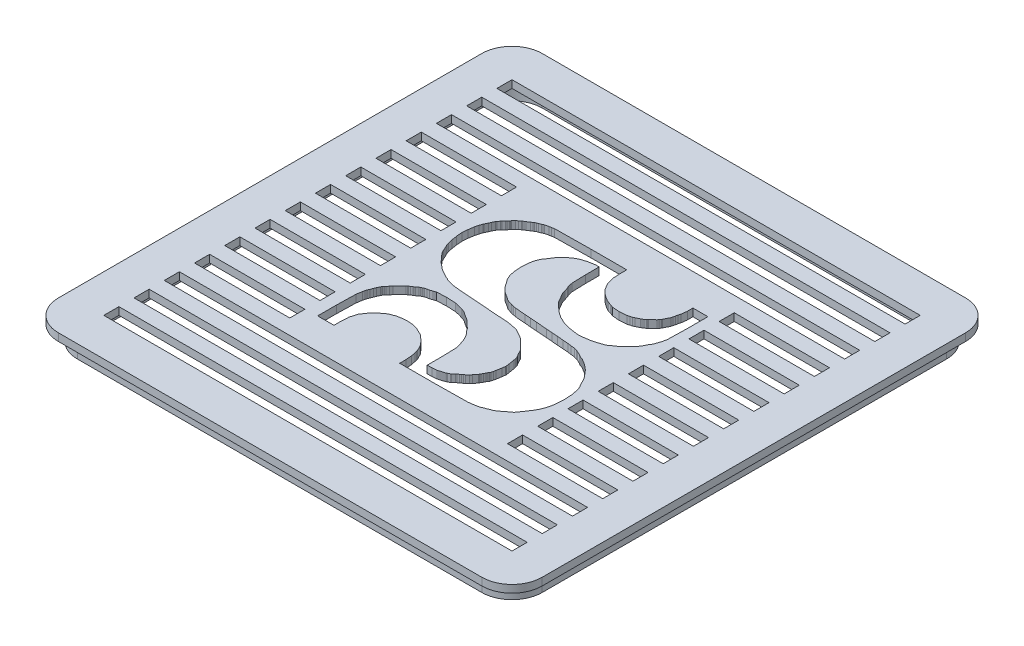
SolidWorks part; units mm, degrees
ref_plane "Front" through (0, 0, 0) normal (0, 0, 1) x (1, 0, 0)
ref_plane "Top" through (0, 0, 0) normal (0, 1, 0) x (1, 0, 0)
ref_plane "Right" through (0, 0, 0) normal (1, 0, 0) x (0, 0, -1)
sketch "Esquisse1" plane through (0, 0, 0) normal (0, 1, 0) x (1, 0, 0)
  line L1 (-50.8, 50.8) -> (50.8, 50.8)
  line L2 (-50.8, 50.8) -> (-50.8, -50.8)
  line L3 (-50.8, -50.8) -> (50.8, -50.8)
  line L4 (50.8, 50.8) -> (50.8, -50.8)
  line L5 (-50.8, 50.8) -> (50.8, -50.8) construction
  line L6 (-50.8, -50.8) -> (50.8, 50.8) construction
  point P0 (0, 0)
  dimension "D1" = 101.6
extrude "Boss.-Extru.1" add sketch "Esquisse1" along normal blind 1.5875
fillet "Congé1" radius 6.35 4 edges at (-50.8, 0.7937, -50.8) (50.8, 0.7937, -50.8) (-50.8, 0.7937, 50.8) (50.8, 0.7937, 50.8)
sketch "Esquisse2" plane through (0, 0, 0) normal (0, -1, 0) x (1, 0, 0)
  line L0 (-50.8, -44.45) -> (-50.8, 44.45) construction
  line L1 (-39.2906, 45.6406) -> (39.2906, 45.6406)
  line L2 (-45.6406, 39.2906) -> (-45.6406, -39.2906)
  line L3 (-39.2906, -45.6406) -> (39.2906, -45.6406)
  line L4 (45.6406, 39.2906) -> (45.6406, -39.2906)
  line L5 (-45.6406, 45.6406) -> (45.6406, -45.6406) construction
  line L6 (-45.6406, -45.6406) -> (45.6406, 45.6406) construction
  line L7 (-42.4656, 48.8156) -> (42.4656, 48.8156)
  line L8 (-48.8156, 42.4656) -> (-48.8156, -42.4656)
  line L9 (-42.4656, -48.8156) -> (42.4656, -48.8156)
  line L10 (48.8156, 42.4656) -> (48.8156, -42.4656)
  line L11 (-48.8156, 48.8156) -> (48.8156, -48.8156) construction
  line L12 (-48.8156, -48.8156) -> (48.8156, 48.8156) construction
  line L13 (44.45, -50.8) -> (-44.45, -50.8) construction
  arc A0 (-45.6406, -39.2906) -> (-39.2906, -45.6406) centre (-39.2906, -39.2906) ccw
  arc A1 (39.2906, -45.6406) -> (45.6406, -39.2906) centre (39.2906, -39.2906) ccw
  arc A2 (39.2906, 45.6406) -> (45.6406, 39.2906) centre (39.2906, 39.2906) cw
  arc A3 (-39.2906, 45.6406) -> (-45.6406, 39.2906) centre (-39.2906, 39.2906) ccw
  arc A4 (-48.8156, -42.4656) -> (-42.4656, -48.8156) centre (-42.4656, -42.4656) ccw
  arc A5 (42.4656, -48.8156) -> (48.8156, -42.4656) centre (42.4656, -42.4656) ccw
  arc A6 (42.4656, 48.8156) -> (48.8156, 42.4656) centre (42.4656, 42.4656) cw
  arc A7 (-42.4656, 48.8156) -> (-48.8156, 42.4656) centre (-42.4656, 42.4656) ccw
  point P0 (0, 0)
  point P6 (0, 0)
  dimension "D5" = 6.35
  dimension "D1" = 1.9844
  dimension "D2" = 1.9844
  dimension "D3" = 3.175
  dimension "D4" = 3.175
extrude "Boss.-Extru.2" add sketch "Esquisse2" along normal blind 3.175
sketch "Esquisse12" plane through (0, 1.5875, 0) normal (0, 1, 0) x (1, 0, 0)
  line L0 (-20.3148, -16.5337) -> (-20.2196, -12.5637)
  line L1 (-20.2196, -12.5637) -> (-20.1244, -11.9493)
  line L2 (-20.1244, -11.9493) -> (-20.0292, -11.3349)
  line L3 (-20.0292, -11.3349) -> (-19.934, -10.9568)
  line L4 (-19.934, -10.9568) -> (-19.8389, -10.5787)
  line L5 (-19.8389, -10.5787) -> (-19.7437, -10.3897)
  line L6 (-19.7437, -10.3897) -> (-19.6485, -10.2006)
  line L7 (-19.6485, -10.2006) -> (-19.5533, -9.917)
  line L8 (-19.5533, -9.917) -> (-19.4581, -9.6335)
  line L9 (-19.4581, -9.6335) -> (-19.3629, -9.3972)
  line L10 (-19.3629, -9.3972) -> (-19.2678, -9.1609)
  line L11 (-19.2678, -9.1609) -> (-19.1726, -8.9718)
  line L12 (-19.1726, -8.9718) -> (-19.0774, -8.7827)
  line L13 (-19.0774, -8.7827) -> (-18.9822, -8.5937)
  line L14 (-18.9822, -8.5937) -> (-18.887, -8.4046)
  line L15 (-18.887, -8.4046) -> (-18.7918, -8.2629)
  line L16 (-18.7918, -8.2629) -> (-18.6491, -8.1211)
  line L17 (-18.6491, -8.1211) -> (-18.5063, -7.9725)
  line L18 (-18.5063, -7.9725) -> (-18.1731, -7.5539)
  line L19 (-18.1731, -7.5539) -> (-17.84, -7.1336)
  line L20 (-17.84, -7.1336) -> (-16.4616, -5.758)
  line L21 (-16.4616, -5.758) -> (-16.317, -5.6635)
  line L22 (-16.317, -5.6635) -> (-16.1953, -5.5689)
  line L23 (-16.1953, -5.5689) -> (-15.9363, -5.3799)
  line L24 (-15.9363, -5.3799) -> (-15.6297, -5.1908)
  line L25 (-15.6297, -5.1908) -> (-15.4603, -5.0963)
  line L26 (-15.4603, -5.0963) -> (-15.3108, -5.0018)
  line L27 (-15.3108, -5.0018) -> (-14.8892, -4.6305)
  line L28 (-14.8892, -4.6305) -> (-14.6988, -4.5292)
  line L29 (-14.6988, -4.5292) -> (-14.5085, -4.4347)
  line L30 (-14.5085, -4.4347) -> (-14.3181, -4.3402)
  line L31 (-14.3181, -4.3402) -> (-14.1278, -4.2456)
  line L32 (-14.1278, -4.2456) -> (-13.6994, -4.1511)
  line L33 (-13.6994, -4.1511) -> (-13.2711, -4.0566)
  line L34 (-13.2711, -4.0566) -> (-12.9855, -3.9621)
  line L35 (-12.9855, -3.9621) -> (-12.7, -3.8676)
  line L36 (-12.7, -3.8676) -> (-12.4144, -3.773)
  line L37 (-12.4144, -3.773) -> (-12.1288, -3.6785)
  line L38 (-12.1288, -3.6785) -> (-10.1775, -3.584)
  line L39 (-10.1775, -3.584) -> (-8.2262, -3.6785)
  line L40 (-8.2262, -3.6785) -> (-7.7503, -3.773)
  line L41 (-7.7503, -3.773) -> (-7.2743, -3.8676)
  line L42 (-7.2743, -3.8676) -> (-6.9888, -3.9621)
  line L43 (-6.9888, -3.9621) -> (-6.7032, -4.0566)
  line L44 (-6.7032, -4.0566) -> (-6.3701, -4.1511)
  line L45 (-6.3701, -4.1511) -> (-6.0369, -4.2456)
  line L46 (-6.0369, -4.2456) -> (-5.8466, -4.3402)
  line L47 (-5.8466, -4.3402) -> (-5.6562, -4.4347)
  line L48 (-5.6562, -4.4347) -> (-5.4658, -4.5292)
  line L49 (-5.4658, -4.5292) -> (-5.2755, -4.671)
  line L50 (-5.2755, -4.671) -> (-5.1061, -4.8128)
  line L51 (-5.1061, -4.8128) -> (-4.7995, -5.0018)
  line L52 (-4.7995, -5.0018) -> (-4.4929, -5.1909)
  line L53 (-4.4929, -5.1909) -> (-4.3236, -5.2854)
  line L54 (-4.3236, -5.2854) -> (-4.1808, -5.3799)
  line L55 (-4.1808, -5.3799) -> (-4.038, -5.4744)
  line L56 (-4.038, -5.4744) -> (-3.8937, -5.569)
  line L57 (-3.8937, -5.569) -> (-2.3247, -7.0589)
  line L58 (-2.3247, -7.0589) -> (-2.1343, -7.2704)
  line L59 (-2.1343, -7.2704) -> (-1.944, -7.5748)
  line L60 (-1.944, -7.5748) -> (-1.7944, -7.743)
  line L61 (-1.7944, -7.743) -> (-1.3728, -8.188)
  line L62 (-1.3728, -8.188) -> (-1.1825, -8.4992)
  line L63 (-1.1825, -8.4992) -> (-0.9921, -8.8036)
  line L64 (-0.9921, -8.8036) -> (-0.8969, -8.9718)
  line L65 (-0.8969, -8.9718) -> (-0.8018, -9.1608)
  line L66 (-0.8018, -9.1608) -> (-0.7066, -9.3499)
  line L67 (-0.7066, -9.3499) -> (-0.6114, -9.5862)
  line L68 (-0.6114, -9.5862) -> (-0.5162, -9.8225)
  line L69 (-0.5162, -9.8225) -> (-0.421, -10.1061)
  line L70 (-0.421, -10.1061) -> (-0.3258, -10.3896)
  line L71 (-0.3258, -10.3896) -> (-0.2307, -10.6732)
  line L72 (-0.2307, -10.6732) -> (-0.1355, -10.9568)
  line L73 (-0.1355, -10.9568) -> (-0.0403, -11.3349)
  line L74 (-0.0403, -11.3349) -> (0.0549, -11.713)
  line L75 (0.0549, -11.713) -> (0.1501, -14.8322)
  line L76 (0.1501, -14.8322) -> (0.1501, -17.951)
  line L77 (0.1501, -17.951) -> (1.1496, -17.951)
  line L78 (1.1496, -17.951) -> (2.149, -17.8565)
  line L79 (2.149, -17.8565) -> (2.4346, -17.762)
  line L80 (2.4346, -17.762) -> (2.7201, -17.6674)
  line L81 (2.7201, -17.6674) -> (3.0533, -17.5729)
  line L82 (3.0533, -17.5729) -> (3.3864, -17.4784)
  line L83 (3.3864, -17.4784) -> (3.5768, -17.3839)
  line L84 (3.5768, -17.3839) -> (3.7672, -17.2893)
  line L85 (3.7672, -17.2893) -> (3.9575, -17.1948)
  line L86 (3.9575, -17.1948) -> (4.1479, -17.1003)
  line L87 (4.1479, -17.1003) -> (4.2975, -17.0058)
  line L88 (4.2975, -17.0058) -> (4.719, -16.5872)
  line L89 (4.719, -16.5872) -> (4.8884, -16.4386)
  line L90 (4.8884, -16.4386) -> (5.1949, -16.2496)
  line L91 (5.1949, -16.2496) -> (5.4329, -16.0606)
  line L92 (5.4329, -16.0606) -> (5.6709, -15.8715)
  line L93 (5.6709, -15.8715) -> (5.9366, -15.6825)
  line L94 (5.9366, -15.6825) -> (6.3372, -15.3044)
  line L95 (6.3372, -15.3044) -> (6.6678, -14.9263)
  line L96 (6.6678, -14.9263) -> (7.1938, -14.2689)
  line L97 (7.1938, -14.2689) -> (7.289, -14.0756)
  line L98 (7.289, -14.0756) -> (7.3842, -13.9074)
  line L99 (7.3842, -13.9074) -> (7.5746, -13.603)
  line L100 (7.5746, -13.603) -> (7.7649, -13.204)
  line L101 (7.7649, -13.204) -> (7.9077, -12.9413)
  line L102 (7.9077, -12.9413) -> (8.0505, -12.7522)
  line L103 (8.0505, -12.7522) -> (8.1457, -12.5632)
  line L104 (8.1457, -12.5632) -> (8.2408, -12.1378)
  line L105 (8.2408, -12.1378) -> (8.336, -11.7125)
  line L106 (8.336, -11.7125) -> (8.4312, -11.1453)
  line L107 (8.4312, -11.1453) -> (8.5264, -10.5782)
  line L108 (8.5264, -10.5782) -> (8.6216, -9.8693)
  line L109 (8.6216, -9.8693) -> (8.5264, -9.1604)
  line L110 (8.5264, -9.1604) -> (8.4312, -8.546)
  line L111 (8.4312, -8.546) -> (8.336, -7.9316)
  line L112 (8.336, -7.9316) -> (8.2408, -7.5535)
  line L113 (8.2408, -7.5535) -> (8.1457, -7.1754)
  line L114 (8.1457, -7.1754) -> (8.0505, -6.9391)
  line L115 (8.0505, -6.9391) -> (7.9077, -6.7028)
  line L116 (7.9077, -6.7028) -> (7.7649, -6.5137)
  line L117 (7.7649, -6.5137) -> (7.6698, -6.3246)
  line L118 (7.6698, -6.3246) -> (7.5746, -6.1356)
  line L119 (7.5746, -6.1356) -> (7.4794, -5.9465)
  line L120 (7.4794, -5.9465) -> (7.3842, -5.7575)
  line L121 (7.3842, -5.7575) -> (7.289, -5.5684)
  line L122 (7.289, -5.5684) -> (7.1938, -5.4223)
  line L123 (7.1938, -5.4223) -> (6.6271, -4.8122)
  line L124 (6.6271, -4.8122) -> (6.5275, -4.7157)
  line L125 (6.5275, -4.7157) -> (5.4084, -3.5834)
  line L126 (5.4084, -3.5834) -> (5.1949, -3.3944)
  line L127 (5.1949, -3.3944) -> (4.9094, -3.2053)
  line L128 (4.9094, -3.2053) -> (4.6238, -3.0163)
  line L129 (4.6238, -3.0163) -> (4.3172, -2.8272)
  line L130 (4.3172, -2.8272) -> (4.1479, -2.7327)
  line L131 (4.1479, -2.7327) -> (3.9575, -2.6382)
  line L132 (3.9575, -2.6382) -> (3.7671, -2.5437)
  line L133 (3.7671, -2.5437) -> (3.5768, -2.4491)
  line L134 (3.5768, -2.4491) -> (3.3864, -2.3074)
  line L135 (3.3864, -2.3074) -> (3.0533, -2.1656)
  line L136 (3.0533, -2.1656) -> (2.7201, -2.0711)
  line L137 (2.7201, -2.0711) -> (2.3394, -1.9765)
  line L138 (2.3394, -1.9765) -> (1.9586, -1.882)
  line L139 (1.9586, -1.882) -> (1.3875, -1.7875)
  line L140 (1.3875, -1.7875) -> (0.8164, -1.693)
  line L141 (0.8164, -1.693) -> (-0.5638, -1.5985)
  line L142 (-0.5638, -1.5985) -> (-1.944, -1.504)
  line L143 (-1.944, -1.504) -> (-3.2291, -1.4094)
  line L144 (-3.2291, -1.4094) -> (-4.5141, -1.3149)
  line L145 (-4.5141, -1.3149) -> (-5.7991, -1.2204)
  line L146 (-5.7991, -1.2204) -> (-7.0841, -1.1259)
  line L147 (-7.0841, -1.1259) -> (-8.3691, -1.0314)
  line L148 (-8.3691, -1.0314) -> (-9.6541, -0.9368)
  line L149 (-9.6541, -0.9368) -> (-10.606, -0.8423)
  line L150 (-10.606, -0.8423) -> (-11.5579, -0.7478)
  line L151 (-11.5579, -0.7478) -> (-11.9386, -0.6533)
  line L152 (-11.9386, -0.6533) -> (-12.3194, -0.5588)
  line L153 (-12.3194, -0.5588) -> (-12.7001, -0.4642)
  line L154 (-12.7001, -0.4642) -> (-13.0809, -0.3697)
  line L155 (-13.0809, -0.3697) -> (-13.2712, -0.2752)
  line L156 (-13.2712, -0.2752) -> (-13.4616, -0.1334)
  line L157 (-13.4616, -0.1334) -> (-13.7947, 0.0084)
  line L158 (-13.7947, 0.0084) -> (-14.1279, 0.1501)
  line L159 (-14.1279, 0.1501) -> (-14.3183, 0.2919)
  line L160 (-14.3183, 0.2919) -> (-14.5086, 0.3865)
  line L161 (-14.5086, 0.3865) -> (-14.699, 0.481)
  line L162 (-14.699, 0.481) -> (-14.8894, 0.5755)
  line L163 (-14.8894, 0.5755) -> (-15.0587, 0.67)
  line L164 (-15.0587, 0.67) -> (-15.3653, 0.8591)
  line L165 (-15.3653, 0.8591) -> (-15.6509, 1.0481)
  line L166 (-15.6509, 1.0481) -> (-15.9364, 1.2372)
  line L167 (-15.9364, 1.2372) -> (-16.1553, 1.4262)
  line L168 (-16.1553, 1.4262) -> (-16.6027, 1.8043)
  line L169 (-16.6027, 1.8043) -> (-17.078, 2.1824)
  line L170 (-17.078, 2.1824) -> (-17.4594, 2.6042)
  line L171 (-17.4594, 2.6042) -> (-18.2177, 3.4112)
  line L172 (-18.2177, 3.4112) -> (-18.3161, 3.5598)
  line L173 (-18.3161, 3.5598) -> (-18.69, 3.9784)
  line L174 (-18.69, 3.9784) -> (-18.792, 4.1674)
  line L175 (-18.792, 4.1674) -> (-18.8872, 4.3565)
  line L176 (-18.8872, 4.3565) -> (-18.9824, 4.5455)
  line L177 (-18.9824, 4.5455) -> (-19.0776, 4.7346)
  line L178 (-19.0776, 4.7346) -> (-19.1727, 4.9709)
  line L179 (-19.1727, 4.9709) -> (-19.2679, 5.2072)
  line L180 (-19.2679, 5.2072) -> (-19.3631, 5.3963)
  line L181 (-19.3631, 5.3963) -> (-19.4583, 5.5853)
  line L182 (-19.4583, 5.5853) -> (-19.5535, 5.7744)
  line L183 (-19.5535, 5.7744) -> (-19.6487, 5.9634)
  line L184 (-19.6487, 5.9634) -> (-19.7438, 6.247)
  line L185 (-19.7438, 6.247) -> (-19.839, 6.5306)
  line L186 (-19.839, 6.5306) -> (-19.9342, 6.9559)
  line L187 (-19.9342, 6.9559) -> (-20.0294, 7.3813)
  line L188 (-20.0294, 7.3813) -> (-20.1246, 7.9957)
  line L189 (-20.1246, 7.9957) -> (-20.2197, 8.6101)
  line L190 (-20.2197, 8.6101) -> (-20.3149, 9.7916)
  line L191 (-20.3149, 9.7916) -> (-20.2197, 10.9731)
  line L192 (-20.2197, 10.9731) -> (-20.1246, 11.5875)
  line L193 (-20.1246, 11.5875) -> (-20.0294, 12.2019)
  line L194 (-20.0294, 12.2019) -> (-19.9342, 12.58)
  line L195 (-19.9342, 12.58) -> (-19.839, 12.9581)
  line L196 (-19.839, 12.9581) -> (-19.7438, 13.2417)
  line L197 (-19.7438, 13.2417) -> (-19.6487, 13.5253)
  line L198 (-19.6487, 13.5253) -> (-19.5535, 13.7143)
  line L199 (-19.5535, 13.7143) -> (-19.4583, 13.9034)
  line L200 (-19.4583, 13.9034) -> (-19.3631, 14.0924)
  line L201 (-19.3631, 14.0924) -> (-19.2679, 14.2815)
  line L202 (-19.2679, 14.2815) -> (-19.1727, 14.5178)
  line L203 (-19.1727, 14.5178) -> (-19.0776, 14.7541)
  line L204 (-19.0776, 14.7541) -> (-18.9824, 14.9431)
  line L205 (-18.9824, 14.9431) -> (-18.8872, 15.1322)
  line L206 (-18.8872, 15.1322) -> (-18.792, 15.3212)
  line L207 (-18.792, 15.3212) -> (-18.69, 15.5103)
  line L208 (-18.69, 15.5103) -> (-18.3161, 15.9289)
  line L209 (-18.3161, 15.9289) -> (-18.2141, 16.0774)
  line L210 (-18.2141, 16.0774) -> (-17.8401, 16.4279)
  line L211 (-17.8401, 16.4279) -> (-17.6498, 16.6445)
  line L212 (-17.6498, 16.6445) -> (-17.4594, 16.9017)
  line L213 (-17.4594, 16.9017) -> (-17.3642, 17.0226)
  line L214 (-17.3642, 17.0226) -> (-17.269, 17.1712)
  line L215 (-17.269, 17.1712) -> (-16.8857, 17.5898)
  line L216 (-16.8857, 17.5898) -> (-16.5076, 17.8733)
  line L217 (-16.5076, 17.8733) -> (-16.1362, 18.1569)
  line L218 (-16.1362, 18.1569) -> (-16.0316, 18.2514)
  line L219 (-16.0316, 18.2514) -> (-15.8623, 18.3459)
  line L220 (-15.8623, 18.3459) -> (-15.5557, 18.535)
  line L221 (-15.5557, 18.535) -> (-15.2702, 18.724)
  line L222 (-15.2702, 18.724) -> (-14.9846, 18.9131)
  line L223 (-14.9846, 18.9131) -> (-14.678, 19.1021)
  line L224 (-14.678, 19.1021) -> (-14.5087, 19.2439)
  line L225 (-14.5087, 19.2439) -> (-14.2231, 19.3857)
  line L226 (-14.2231, 19.3857) -> (-13.9375, 19.4802)
  line L227 (-13.9375, 19.4802) -> (-13.6996, 19.5747)
  line L228 (-13.6996, 19.5747) -> (-13.4616, 19.6692)
  line L229 (-13.4616, 19.6692) -> (-13.2712, 19.7637)
  line L230 (-13.2712, 19.7637) -> (-13.0809, 19.8582)
  line L231 (-13.0809, 19.8582) -> (-12.7001, 19.9527)
  line L232 (-12.7001, 19.9527) -> (-12.3194, 20.0473)
  line L233 (-12.3194, 20.0473) -> (-11.7959, 20.1418)
  line L234 (-11.7959, 20.1418) -> (-11.2723, 20.2363)
  line L235 (-11.2723, 20.2363) -> (-3.7526, 20.3308)
  line L236 (-3.7526, 20.3308) -> (3.7672, 20.3304)
  line L237 (3.7672, 20.3304) -> (3.7672, 18.7706)
  line L238 (3.7672, 18.7706) -> (3.8624, 17.2109)
  line L239 (3.8624, 17.2109) -> (3.9575, 16.8801)
  line L240 (3.9575, 16.8801) -> (4.0527, 16.5493)
  line L241 (4.0527, 16.5493) -> (4.1479, 16.2184)
  line L242 (4.1479, 16.2184) -> (4.2431, 15.8876)
  line L243 (4.2431, 15.8876) -> (4.3383, 15.6986)
  line L244 (4.3383, 15.6986) -> (4.4335, 15.5095)
  line L245 (4.4335, 15.5095) -> (4.5286, 15.3413)
  line L246 (4.5286, 15.3413) -> (4.719, 15.0369)
  line L247 (4.719, 15.0369) -> (4.9094, 14.7325)
  line L248 (4.9094, 14.7325) -> (5.0045, 14.5643)
  line L249 (5.0045, 14.5643) -> (5.0997, 14.463)
  line L250 (5.0997, 14.463) -> (5.4323, 14.0917)
  line L251 (5.4323, 14.0917) -> (5.9564, 13.6191)
  line L252 (5.9564, 13.6191) -> (6.5955, 13.1464)
  line L253 (6.5955, 13.1464) -> (6.9083, 12.9574)
  line L254 (6.9083, 12.9574) -> (7.2148, 12.7683)
  line L255 (7.2148, 12.7683) -> (7.3842, 12.6738)
  line L256 (7.3842, 12.6738) -> (7.5746, 12.5793)
  line L257 (7.5746, 12.5793) -> (7.7649, 12.4848)
  line L258 (7.7649, 12.4848) -> (8.0981, 12.3903)
  line L259 (8.0981, 12.3903) -> (8.4312, 12.2958)
  line L260 (8.4312, 12.2958) -> (8.7168, 12.2013)
  line L261 (8.7168, 12.2013) -> (9.0023, 12.0595)
  line L262 (9.0023, 12.0595) -> (10.5729, 11.9177)
  line L263 (10.5729, 11.9177) -> (12.1435, 12.0595)
  line L264 (12.1435, 12.0595) -> (12.5718, 12.2013)
  line L265 (12.5718, 12.2013) -> (13.0002, 12.2958)
  line L266 (13.0002, 12.2958) -> (13.1905, 12.3903)
  line L267 (13.1905, 12.3903) -> (13.3809, 12.4848)
  line L268 (13.3809, 12.4848) -> (13.5713, 12.5793)
  line L269 (13.5713, 12.5793) -> (13.7616, 12.6738)
  line L270 (13.7616, 12.6738) -> (13.952, 12.7683)
  line L271 (13.952, 12.7683) -> (14.1424, 12.8629)
  line L272 (14.1424, 12.8629) -> (14.3117, 12.9574)
  line L273 (14.3117, 12.9574) -> (14.6183, 13.1464)
  line L274 (14.6183, 13.1464) -> (14.8773, 13.3355)
  line L275 (14.8773, 13.3355) -> (14.999, 13.43)
  line L276 (14.999, 13.43) -> (15.0967, 13.5245)
  line L277 (15.0967, 13.5245) -> (16.0461, 14.4464)
  line L278 (16.0461, 14.4464) -> (16.2365, 14.6588)
  line L279 (16.2365, 14.6588) -> (16.4268, 14.9632)
  line L280 (16.4268, 14.9632) -> (16.522, 15.1314)
  line L281 (16.522, 15.1314) -> (16.6172, 15.3204)
  line L282 (16.6172, 15.3204) -> (16.7124, 15.5095)
  line L283 (16.7124, 15.5095) -> (16.8076, 15.6985)
  line L284 (16.8076, 15.6985) -> (16.9027, 15.8876)
  line L285 (16.9027, 15.8876) -> (16.9979, 16.0766)
  line L286 (16.9979, 16.0766) -> (17.0931, 16.2657)
  line L287 (17.0931, 16.2657) -> (17.1883, 16.6438)
  line L288 (17.1883, 16.6438) -> (17.2835, 17.0219)
  line L289 (17.2835, 17.0219) -> (17.3787, 17.4945)
  line L290 (17.3787, 17.4945) -> (17.5214, 17.9671)
  line L291 (17.5214, 17.9671) -> (17.6642, 19.1486)
  line L292 (17.6642, 19.1486) -> (17.6642, 20.3304)
  line L293 (17.6642, 20.3304) -> (19.2348, 20.3304)
  line L294 (19.2348, 20.3304) -> (20.8053, 20.3304)
  line L295 (20.8053, 20.3304) -> (20.8053, 16.1241)
  line L296 (20.8053, 16.1241) -> (20.7102, 11.9179)
  line L297 (20.7102, 11.9179) -> (20.615, 11.4452)
  line L298 (20.615, 11.4452) -> (20.5198, 10.9726)
  line L299 (20.5198, 10.9726) -> (20.4246, 10.6891)
  line L300 (20.4246, 10.6891) -> (20.3294, 10.4055)
  line L301 (20.3294, 10.4055) -> (20.2342, 10.1219)
  line L302 (20.2342, 10.1219) -> (20.1391, 9.8383)
  line L303 (20.1391, 9.8383) -> (20.0439, 9.602)
  line L304 (20.0439, 9.602) -> (19.9011, 9.3657)
  line L305 (19.9011, 9.3657) -> (19.7583, 9.1767)
  line L306 (19.7583, 9.1767) -> (19.6632, 8.9876)
  line L307 (19.6632, 8.9876) -> (19.568, 8.7986)
  line L308 (19.568, 8.7986) -> (19.4728, 8.6095)
  line L309 (19.4728, 8.6095) -> (19.3776, 8.4205)
  line L310 (19.3776, 8.4205) -> (19.2824, 8.2314)
  line L311 (19.2824, 8.2314) -> (19.1872, 8.0896)
  line L312 (19.1872, 8.0896) -> (19.0921, 7.9478)
  line L313 (19.0921, 7.9478) -> (18.9969, 7.7797)
  line L314 (18.9969, 7.7797) -> (18.8065, 7.4752)
  line L315 (18.8065, 7.4752) -> (18.6161, 7.2633)
  line L316 (18.6161, 7.2633) -> (17.5174, 6.1519)
  line L317 (17.5174, 6.1519) -> (16.998, 5.6793)
  line L318 (16.998, 5.6793) -> (16.3854, 5.2067)
  line L319 (16.3854, 5.2067) -> (16.2365, 5.1122)
  line L320 (16.2365, 5.1122) -> (16.0461, 5.0176)
  line L321 (16.0461, 5.0176) -> (15.8557, 4.9164)
  line L322 (15.8557, 4.9164) -> (15.4342, 4.545)
  line L323 (15.4342, 4.545) -> (15.2846, 4.4505)
  line L324 (15.2846, 4.4505) -> (14.999, 4.356)
  line L325 (14.999, 4.356) -> (14.7135, 4.2614)
  line L326 (14.7135, 4.2614) -> (14.4279, 4.1669)
  line L327 (14.4279, 4.1669) -> (14.1424, 4.0724)
  line L328 (14.1424, 4.0724) -> (13.8568, 3.9779)
  line L329 (13.8568, 3.9779) -> (13.5713, 3.8834)
  line L330 (13.5713, 3.8834) -> (13.1905, 3.7888)
  line L331 (13.1905, 3.7888) -> (12.8098, 3.6943)
  line L332 (12.8098, 3.6943) -> (12.191, 3.5998)
  line L333 (12.191, 3.5998) -> (11.5723, 3.5053)
  line L334 (11.5723, 3.5053) -> (10.5729, 3.4107)
  line L335 (10.5729, 3.4107) -> (9.5734, 3.5053)
  line L336 (9.5734, 3.5053) -> (9.0023, 3.5998)
  line L337 (9.0023, 3.5998) -> (8.4312, 3.6943)
  line L338 (8.4312, 3.6943) -> (8.0029, 3.7888)
  line L339 (8.0029, 3.7888) -> (7.5745, 3.8834)
  line L340 (7.5745, 3.8834) -> (7.289, 3.9779)
  line L341 (7.289, 3.9779) -> (7.0034, 4.0724)
  line L342 (7.0034, 4.0724) -> (6.7654, 4.1669)
  line L343 (6.7654, 4.1669) -> (6.5275, 4.2614)
  line L344 (6.5275, 4.2614) -> (6.3371, 4.356)
  line L345 (6.3371, 4.356) -> (6.1467, 4.4505)
  line L346 (6.1467, 4.4505) -> (5.9564, 4.545)
  line L347 (5.9564, 4.545) -> (5.766, 4.6395)
  line L348 (5.766, 4.6395) -> (5.528, 4.7341)
  line L349 (5.528, 4.7341) -> (5.2901, 4.8758)
  line L350 (5.2901, 4.8758) -> (5.1207, 5.0176)
  line L351 (5.1207, 5.0176) -> (4.8141, 5.2067)
  line L352 (4.8141, 5.2067) -> (4.5506, 5.3957)
  line L353 (4.5506, 5.3957) -> (3.7671, 6.0574)
  line L354 (3.7671, 6.0574) -> (3.0535, 6.7191)
  line L355 (3.0535, 6.7191) -> (2.5297, 7.2819)
  line L356 (2.5297, 7.2819) -> (2.4345, 7.3807)
  line L357 (2.4345, 7.3807) -> (2.3393, 7.5489)
  line L358 (2.3393, 7.5489) -> (2.1489, 7.8533)
  line L359 (2.1489, 7.8533) -> (1.9586, 8.1842)
  line L360 (1.9586, 8.1842) -> (1.7682, 8.515)
  line L361 (1.7682, 8.515) -> (1.5778, 8.8194)
  line L362 (1.5778, 8.8194) -> (1.4827, 8.9876)
  line L363 (1.4827, 8.9876) -> (1.3875, 9.1766)
  line L364 (1.3875, 9.1766) -> (1.2923, 9.3657)
  line L365 (1.2923, 9.3657) -> (1.1971, 9.6965)
  line L366 (1.1971, 9.6965) -> (1.1019, 10.0274)
  line L367 (1.1019, 10.0274) -> (1.0067, 10.3109)
  line L368 (1.0067, 10.3109) -> (0.9116, 10.5945)
  line L369 (0.9116, 10.5945) -> (0.8164, 10.8781)
  line L370 (0.8164, 10.8781) -> (0.6736, 11.1616)
  line L371 (0.6736, 11.1616) -> (0.5308, 11.6815)
  line L372 (0.5308, 11.6815) -> (0.4357, 12.2014)
  line L373 (0.4357, 12.2014) -> (0.3405, 15.0844)
  line L374 (0.3405, 15.0844) -> (0.3405, 17.9674)
  line L375 (0.3405, 17.9674) -> (-0.3259, 17.9674)
  line L376 (-0.3259, 17.9674) -> (-0.9922, 17.8729)
  line L377 (-0.9922, 17.8729) -> (-1.4681, 17.7784)
  line L378 (-1.4681, 17.7784) -> (-1.9441, 17.6839)
  line L379 (-1.9441, 17.6839) -> (-2.2296, 17.5893)
  line L380 (-2.2296, 17.5893) -> (-2.5152, 17.4948)
  line L381 (-2.5152, 17.4948) -> (-2.8008, 17.4003)
  line L382 (-2.8008, 17.4003) -> (-3.0863, 17.3058)
  line L383 (-3.0863, 17.3058) -> (-3.2767, 17.2113)
  line L384 (-3.2767, 17.2113) -> (-3.467, 17.1168)
  line L385 (-3.467, 17.1168) -> (-3.6574, 17.0223)
  line L386 (-3.6574, 17.0223) -> (-3.8478, 16.921)
  line L387 (-3.8478, 16.921) -> (-4.3169, 16.5497)
  line L388 (-4.3169, 16.5497) -> (-4.5141, 16.4508)
  line L389 (-4.5141, 16.4508) -> (-5.0834, 15.888)
  line L390 (-5.0834, 15.888) -> (-6.0371, 14.9189)
  line L391 (-6.0371, 14.9189) -> (-6.2274, 14.6592)
  line L392 (-6.2274, 14.6592) -> (-6.4178, 14.3075)
  line L393 (-6.4178, 14.3075) -> (-6.5198, 14.0921)
  line L394 (-6.5198, 14.0921) -> (-6.8937, 13.6735)
  line L395 (-6.8937, 13.6735) -> (-6.9889, 13.5249)
  line L396 (-6.9889, 13.5249) -> (-7.0841, 13.3359)
  line L397 (-7.0841, 13.3359) -> (-7.1793, 13.1468)
  line L398 (-7.1793, 13.1468) -> (-7.2745, 12.9578)
  line L399 (-7.2745, 12.9578) -> (-7.3696, 12.7687)
  line L400 (-7.3696, 12.7687) -> (-7.4648, 12.4852)
  line L401 (-7.4648, 12.4852) -> (-7.56, 12.2016)
  line L402 (-7.56, 12.2016) -> (-7.6552, 11.7762)
  line L403 (-7.6552, 11.7762) -> (-7.7504, 11.3509)
  line L404 (-7.7504, 11.3509) -> (-7.8456, 9.7913)
  line L405 (-7.8456, 9.7913) -> (-7.7504, 8.2316)
  line L406 (-7.7504, 8.2316) -> (-7.6552, 7.8063)
  line L407 (-7.6552, 7.8063) -> (-7.56, 7.3809)
  line L408 (-7.56, 7.3809) -> (-7.4648, 7.0501)
  line L409 (-7.4648, 7.0501) -> (-7.3696, 6.7193)
  line L410 (-7.3696, 6.7193) -> (-7.2745, 6.5302)
  line L411 (-7.2745, 6.5302) -> (-7.1793, 6.3412)
  line L412 (-7.1793, 6.3412) -> (-7.0841, 6.1521)
  line L413 (-7.0841, 6.1521) -> (-6.9889, 5.9631)
  line L414 (-6.9889, 5.9631) -> (-6.8937, 5.8145)
  line L415 (-6.8937, 5.8145) -> (-6.5198, 5.3959)
  line L416 (-6.5198, 5.3959) -> (-6.4178, 5.2069)
  line L417 (-6.4178, 5.2069) -> (-6.3226, 5.0178)
  line L418 (-6.3226, 5.0178) -> (-6.2274, 4.8969)
  line L419 (-6.2274, 4.8969) -> (-6.0371, 4.6397)
  line L420 (-6.0371, 4.6397) -> (-5.8467, 4.3794)
  line L421 (-5.8467, 4.3794) -> (-5.079, 3.6)
  line L422 (-5.079, 3.6) -> (-4.7045, 3.3164)
  line L423 (-4.7045, 3.3164) -> (-4.259, 3.0328)
  line L424 (-4.259, 3.0328) -> (-3.943, 2.8438)
  line L425 (-3.943, 2.8438) -> (-3.6364, 2.6547)
  line L426 (-3.6364, 2.6547) -> (-3.4671, 2.513)
  line L427 (-3.4671, 2.513) -> (-3.2767, 2.3712)
  line L428 (-3.2767, 2.3712) -> (-3.0863, 2.2766)
  line L429 (-3.0863, 2.2766) -> (-2.8008, 2.1821)
  line L430 (-2.8008, 2.1821) -> (-2.5152, 2.0876)
  line L431 (-2.5152, 2.0876) -> (-2.2296, 1.9931)
  line L432 (-2.2296, 1.9931) -> (-1.9441, 1.8986)
  line L433 (-1.9441, 1.8986) -> (-1.4682, 1.804)
  line L434 (-1.4682, 1.804) -> (-0.9922, 1.7095)
  line L435 (-0.9922, 1.7095) -> (0.1024, 1.615)
  line L436 (0.1024, 1.615) -> (1.1971, 1.5205)
  line L437 (1.1971, 1.5205) -> (2.4821, 1.426)
  line L438 (2.4821, 1.426) -> (3.7671, 1.3314)
  line L439 (3.7671, 1.3314) -> (4.9569, 1.2369)
  line L440 (4.9569, 1.2369) -> (6.1468, 1.1424)
  line L441 (6.1468, 1.1424) -> (7.3842, 1.0479)
  line L442 (7.3842, 1.0479) -> (8.6216, 0.9534)
  line L443 (8.6216, 0.9534) -> (9.8114, 0.8588)
  line L444 (9.8114, 0.8588) -> (11.0013, 0.7643)
  line L445 (11.0013, 0.7643) -> (11.7628, 0.6698)
  line L446 (11.7628, 0.6698) -> (12.5243, 0.5753)
  line L447 (12.5243, 0.5753) -> (12.8574, 0.4808)
  line L448 (12.8574, 0.4808) -> (13.1906, 0.3862)
  line L449 (13.1906, 0.3862) -> (13.4761, 0.2917)
  line L450 (13.4761, 0.2917) -> (13.7617, 0.1499)
  line L451 (13.7617, 0.1499) -> (14.0472, 0.0082)
  line L452 (14.0472, 0.0082) -> (14.3328, -0.1336)
  line L453 (14.3328, -0.1336) -> (14.5232, -0.2754)
  line L454 (14.5232, -0.2754) -> (14.7135, -0.3699)
  line L455 (14.7135, -0.3699) -> (14.9991, -0.4644)
  line L456 (14.9991, -0.4644) -> (15.2847, -0.559)
  line L457 (15.2847, -0.559) -> (15.454, -0.6535)
  line L458 (15.454, -0.6535) -> (15.7606, -0.8426)
  line L459 (15.7606, -0.8426) -> (16.0672, -1.0316)
  line L460 (16.0672, -1.0316) -> (16.2365, -1.1261)
  line L461 (16.2365, -1.1261) -> (16.3855, -1.2206)
  line L462 (16.3855, -1.2206) -> (16.998, -1.6933)
  line L463 (16.998, -1.6933) -> (17.5629, -2.1659)
  line L464 (17.5629, -2.1659) -> (17.6643, -2.2656)
  line L465 (17.6643, -2.2656) -> (18.2354, -2.9221)
  line L466 (18.2354, -2.9221) -> (18.8065, -3.6049)
  line L467 (18.8065, -3.6049) -> (18.9969, -3.8673)
  line L468 (18.9969, -3.8673) -> (19.1873, -4.1717)
  line L469 (19.1873, -4.1717) -> (19.2824, -4.3399)
  line L470 (19.2824, -4.3399) -> (19.3776, -4.5553)
  line L471 (19.3776, -4.5553) -> (19.568, -4.907)
  line L472 (19.568, -4.907) -> (19.7584, -5.306)
  line L473 (19.7584, -5.306) -> (19.9011, -5.5687)
  line L474 (19.9011, -5.5687) -> (20.0439, -5.7578)
  line L475 (20.0439, -5.7578) -> (20.1391, -5.9468)
  line L476 (20.1391, -5.9468) -> (20.2343, -6.1359)
  line L477 (20.2343, -6.1359) -> (20.3295, -6.3249)
  line L478 (20.3295, -6.3249) -> (20.4246, -6.7503)
  line L479 (20.4246, -6.7503) -> (20.5198, -7.1756)
  line L480 (20.5198, -7.1756) -> (20.615, -7.6482)
  line L481 (20.615, -7.6482) -> (20.7102, -8.1209)
  line L482 (20.7102, -8.1209) -> (20.8054, -9.8223)
  line L483 (20.8054, -9.8223) -> (20.7102, -11.5237)
  line L484 (20.7102, -11.5237) -> (20.615, -12.0436)
  line L485 (20.615, -12.0436) -> (20.5198, -12.5634)
  line L486 (20.5198, -12.5634) -> (20.4246, -12.9415)
  line L487 (20.4246, -12.9415) -> (20.3295, -13.3196)
  line L488 (20.3295, -13.3196) -> (20.2343, -13.5087)
  line L489 (20.2343, -13.5087) -> (20.1391, -13.6977)
  line L490 (20.1391, -13.6977) -> (20.0439, -14.0286)
  line L491 (20.0439, -14.0286) -> (19.9011, -14.3594)
  line L492 (19.9011, -14.3594) -> (19.7584, -14.5484)
  line L493 (19.7584, -14.5484) -> (19.6632, -14.7375)
  line L494 (19.6632, -14.7375) -> (19.568, -14.9057)
  line L495 (19.568, -14.9057) -> (19.3776, -15.2101)
  line L496 (19.3776, -15.2101) -> (19.1873, -15.4937)
  line L497 (19.1873, -15.4937) -> (18.9969, -15.7772)
  line L498 (18.9969, -15.7772) -> (18.8065, -16.0608)
  line L499 (18.8065, -16.0608) -> (18.6162, -16.3444)
  line L500 (18.6162, -16.3444) -> (18.4258, -16.6109)
  line L501 (18.4258, -16.6109) -> (18.1402, -17.006)
  line L502 (18.1402, -17.006) -> (17.8547, -17.4221)
  line L503 (17.8547, -17.4221) -> (17.6581, -17.5732)
  line L504 (17.6581, -17.5732) -> (16.998, -18.0458)
  line L505 (16.998, -18.0458) -> (16.4065, -18.5184)
  line L506 (16.4065, -18.5184) -> (16.1413, -18.7075)
  line L507 (16.1413, -18.7075) -> (15.8347, -18.8965)
  line L508 (15.8347, -18.8965) -> (15.6654, -19.0383)
  line L509 (15.6654, -19.0383) -> (15.475, -19.1801)
  line L510 (15.475, -19.1801) -> (15.2847, -19.2746)
  line L511 (15.2847, -19.2746) -> (14.9991, -19.3691)
  line L512 (14.9991, -19.3691) -> (14.7135, -19.4637)
  line L513 (14.7135, -19.4637) -> (14.5232, -19.5582)
  line L514 (14.5232, -19.5582) -> (14.3328, -19.6527)
  line L515 (14.3328, -19.6527) -> (14.0473, -19.7472)
  line L516 (14.0473, -19.7472) -> (13.7617, -19.8417)
  line L517 (13.7617, -19.8417) -> (13.5713, -19.9363)
  line L518 (13.5713, -19.9363) -> (13.3809, -20.0308)
  line L519 (13.3809, -20.0308) -> (12.9526, -20.1253)
  line L520 (12.9526, -20.1253) -> (12.5243, -20.2198)
  line L521 (12.5243, -20.2198) -> (11.858, -20.3143)
  line L522 (11.858, -20.3143) -> (11.1917, -20.4089)
  line L523 (11.1917, -20.4089) -> (4.0527, -20.5034)
  line L524 (4.0527, -20.5034) -> (-3.0859, -20.5029)
  line L525 (-3.0859, -20.5029) -> (-3.0859, -19.2273)
  line L526 (-3.0859, -19.2273) -> (-3.1811, -17.9513)
  line L527 (-3.1811, -17.9513) -> (-3.2763, -17.4787)
  line L528 (-3.2763, -17.4787) -> (-3.3715, -17.006)
  line L529 (-3.3715, -17.006) -> (-3.4667, -16.6279)
  line L530 (-3.4667, -16.6279) -> (-3.5619, -16.2499)
  line L531 (-3.5619, -16.2499) -> (-3.657, -16.0608)
  line L532 (-3.657, -16.0608) -> (-3.7522, -15.8718)
  line L533 (-3.7522, -15.8718) -> (-3.8474, -15.6827)
  line L534 (-3.8474, -15.6827) -> (-3.9426, -15.4936)
  line L535 (-3.9426, -15.4936) -> (-4.0378, -15.3046)
  line L536 (-4.0378, -15.3046) -> (-4.1397, -15.1155)
  line L537 (-4.1397, -15.1155) -> (-4.5137, -14.7178)
  line L538 (-4.5137, -14.7178) -> (-4.7041, -14.4539)
  line L539 (-4.7041, -14.4539) -> (-4.8944, -14.2415)
  line L540 (-4.8944, -14.2415) -> (-5.8704, -13.3196)
  line L541 (-5.8704, -13.3196) -> (-6.1319, -13.1305)
  line L542 (-6.1319, -13.1305) -> (-6.486, -12.9415)
  line L543 (-6.486, -12.9415) -> (-6.703, -12.847)
  line L544 (-6.703, -12.847) -> (-6.8933, -12.7525)
  line L545 (-6.8933, -12.7525) -> (-7.0837, -12.6579)
  line L546 (-7.0837, -12.6579) -> (-7.2741, -12.5634)
  line L547 (-7.2741, -12.5634) -> (-7.4645, -12.4689)
  line L548 (-7.4645, -12.4689) -> (-7.75, -12.3744)
  line L549 (-7.75, -12.3744) -> (-8.0356, -12.2799)
  line L550 (-8.0356, -12.2799) -> (-8.4163, -12.1853)
  line L551 (-8.4163, -12.1853) -> (-8.7971, -12.0908)
  line L552 (-8.7971, -12.0908) -> (-9.9393, -11.9963)
  line L553 (-9.9393, -11.9963) -> (-11.0815, -12.0908)
  line L554 (-11.0815, -12.0908) -> (-11.6051, -12.1853)
  line L555 (-11.6051, -12.1853) -> (-12.1286, -12.2799)
  line L556 (-12.1286, -12.2799) -> (-12.3189, -12.3744)
  line L557 (-12.3189, -12.3744) -> (-12.5093, -12.4689)
  line L558 (-12.5093, -12.4689) -> (-12.7949, -12.5634)
  line L559 (-12.7949, -12.5634) -> (-13.0804, -12.6579)
  line L560 (-13.0804, -12.6579) -> (-13.2498, -12.7525)
  line L561 (-13.2498, -12.7525) -> (-13.5564, -12.9415)
  line L562 (-13.5564, -12.9415) -> (-13.865, -13.1306)
  line L563 (-13.865, -13.1306) -> (-15.0793, -14.2229)
  line L564 (-15.0793, -14.2229) -> (-15.4601, -14.6429)
  line L565 (-15.4601, -14.6429) -> (-15.8408, -15.1554)
  line L566 (-15.8408, -15.1554) -> (-15.936, -15.3046)
  line L567 (-15.936, -15.3046) -> (-16.0312, -15.4937)
  line L568 (-16.0312, -15.4937) -> (-16.174, -15.6827)
  line L569 (-16.174, -15.6827) -> (-16.3167, -15.8718)
  line L570 (-16.3167, -15.8718) -> (-16.4119, -16.0608)
  line L571 (-16.4119, -16.0608) -> (-16.5071, -16.4389)
  line L572 (-16.5071, -16.4389) -> (-16.6023, -16.817)
  line L573 (-16.6023, -16.817) -> (-16.6975, -17.1006)
  line L574 (-16.6975, -17.1006) -> (-16.7927, -17.3841)
  line L575 (-16.7927, -17.3841) -> (-16.8878, -18.9438)
  line L576 (-16.8878, -18.9438) -> (-16.8878, -20.5029)
  line L577 (-16.8878, -20.5029) -> (-18.6012, -20.5029)
  line L578 (-18.6012, -20.5029) -> (-20.3145, -20.5029)
  line L579 (-20.3145, -20.5029) -> (-20.3148, -16.5337)
extrude "Enlèv. mat.-Extru.3" cut sketch "Esquisse12" against normal blind 3.175
sketch "Esquisse14" plane through (0, 0, 0) normal (0, -1, 0) x (1, 0, 0)
  line L0 (-42.8625, 36.5125) -> (42.8625, 36.5125)
  line L1 (-22.86, 22.86) -> (22.86, 22.86) construction
  line L2 (-22.86, 22.86) -> (-22.86, -22.86) construction
  line L3 (-22.86, -22.86) -> (22.86, -22.86) construction
  line L4 (22.86, 22.86) -> (22.86, -22.86) construction
  line L5 (-22.86, 22.86) -> (22.86, -22.86) construction
  line L6 (-22.86, -22.86) -> (22.86, 22.86) construction
  line L7 (-42.8625, 42.8625) -> (42.8625, 42.8625) construction
  line L8 (-42.8625, 42.8625) -> (-42.8625, -42.8625) construction
  line L9 (-42.8625, -42.8625) -> (42.8625, -42.8625) construction
  line L10 (42.8625, 42.8625) -> (42.8625, -42.8625) construction
  line L11 (-42.8625, 42.8625) -> (42.8625, -42.8625) construction
  line L12 (-42.8625, -42.8625) -> (42.8625, 42.8625) construction
  line L13 (42.8625, 36.5125) -> (42.8625, 33.3375)
  line L15 (42.8625, 42.8625) -> (42.8625, 39.6875)
  line L16 (42.8625, 39.6875) -> (-42.8625, 39.6875)
  line L17 (-42.8625, 39.6875) -> (-42.8625, 42.8625)
  line L50 (-42.8625, 42.8625) -> (42.8625, 42.8625)
  line L51 (42.8625, 33.3375) -> (-42.8625, 33.3375)
  line L52 (-42.8625, 33.3375) -> (-42.8625, 36.5125)
  line L53 (-42.8625, 30.1625) -> (42.8625, 30.1625)
  line L54 (42.8625, 30.1625) -> (42.8625, 26.9875)
  line L55 (42.8625, 26.9875) -> (-42.8625, 26.9875)
  line L56 (-42.8625, 26.9875) -> (-42.8625, 30.1625)
  line L57 (-42.8625, 23.8125) -> (-22.86, 23.8125)
  line L58 (42.8625, 23.8125) -> (42.8625, 20.6375)
  line L59 (42.8625, 20.6375) -> (22.86, 20.6375)
  line L60 (-42.8625, 20.6375) -> (-42.8625, 23.8125)
  line L61 (-42.8625, 17.4625) -> (-22.86, 17.4625)
  line L62 (42.8625, 17.4625) -> (42.8625, 14.2875)
  line L63 (42.8625, 14.2875) -> (22.86, 14.2875)
  line L64 (-42.8625, 14.2875) -> (-42.8625, 17.4625)
  line L65 (-42.8625, 11.1125) -> (-22.86, 11.1125)
  line L66 (42.8625, 11.1125) -> (42.8625, 7.9375)
  line L67 (42.8625, 7.9375) -> (22.86, 7.9375)
  line L68 (-42.8625, 7.9375) -> (-42.8625, 11.1125)
  line L69 (-42.8625, 4.7625) -> (-22.86, 4.7625)
  line L70 (42.8625, 4.7625) -> (42.8625, 1.5875)
  line L71 (42.8625, 1.5875) -> (22.86, 1.5875)
  line L72 (-42.8625, 1.5875) -> (-42.8625, 4.7625)
  line L73 (-42.8625, -1.5875) -> (-22.86, -1.5875)
  line L74 (42.8625, -1.5875) -> (42.8625, -4.7625)
  line L75 (42.8625, -4.7625) -> (22.86, -4.7625)
  line L76 (-42.8625, -4.7625) -> (-42.8625, -1.5875)
  line L77 (-42.8625, -7.9375) -> (-22.86, -7.9375)
  line L78 (42.8625, -7.9375) -> (42.8625, -11.1125)
  line L79 (42.8625, -11.1125) -> (22.86, -11.1125)
  line L80 (-42.8625, -11.1125) -> (-42.8625, -7.9375)
  line L81 (-42.8625, -14.2875) -> (-22.86, -14.2875)
  line L82 (42.8625, -14.2875) -> (42.8625, -17.4625)
  line L83 (42.8625, -17.4625) -> (22.86, -17.4625)
  line L84 (-42.8625, -17.4625) -> (-42.8625, -14.2875)
  line L85 (-42.8625, -20.6375) -> (-22.86, -20.6375)
  line L86 (42.8625, -20.6375) -> (42.8625, -23.8125)
  line L87 (42.8625, -23.8125) -> (22.86, -23.8125)
  line L88 (-42.8625, -23.8125) -> (-42.8625, -20.6375)
  line L89 (-42.8625, -26.9875) -> (42.8625, -26.9875)
  line L90 (42.8625, -26.9875) -> (42.8625, -30.1625)
  line L91 (42.8625, -30.1625) -> (-42.8625, -30.1625)
  line L92 (-42.8625, -30.1625) -> (-42.8625, -26.9875)
  line L93 (-42.8625, -33.3375) -> (42.8625, -33.3375)
  line L94 (42.8625, -33.3375) -> (42.8625, -36.5125)
  line L95 (42.8625, -36.5125) -> (-42.8625, -36.5125)
  line L96 (-42.8625, -36.5125) -> (-42.8625, -33.3375)
  line L97 (-42.8625, -39.6875) -> (42.8625, -39.6875)
  line L98 (42.8625, -39.6875) -> (42.8625, -42.8625)
  line L99 (42.8625, -42.8625) -> (-42.8625, -42.8625)
  line L100 (-42.8625, -42.8625) -> (-42.8625, -39.6875)
  line L102 (22.86, -23.8125) -> (22.86, -20.6375)
  line L103 (-22.86, 23.8125) -> (-22.86, 20.6375)
  line L104 (22.86, 23.8125) -> (42.8625, 23.8125)
  line L105 (-22.86, 20.6375) -> (-42.8625, 20.6375)
  line L106 (22.86, 20.6375) -> (22.86, 23.8125)
  line L107 (-22.86, 17.4625) -> (-22.86, 14.2875)
  line L108 (-22.86, 14.2875) -> (-42.8625, 14.2875)
  line L109 (22.86, 17.4625) -> (42.8625, 17.4625)
  line L110 (22.86, 11.1125) -> (42.8625, 11.1125)
  line L111 (-22.86, 7.9375) -> (-42.8625, 7.9375)
  line L112 (22.86, 4.7625) -> (42.8625, 4.7625)
  line L113 (-22.86, 1.5875) -> (-42.8625, 1.5875)
  line L114 (-22.86, -4.7625) -> (-42.8625, -4.7625)
  line L115 (22.86, -1.5875) -> (42.8625, -1.5875)
  line L116 (22.86, -7.9375) -> (42.8625, -7.9375)
  line L117 (-22.86, -11.1125) -> (-42.8625, -11.1125)
  line L118 (22.86, -14.2875) -> (42.8625, -14.2875)
  line L119 (-22.86, -17.4625) -> (-42.8625, -17.4625)
  line L120 (22.86, 14.2875) -> (22.86, 17.4625)
  line L121 (22.86, 7.9375) -> (22.86, 11.1125)
  line L122 (22.86, 1.5875) -> (22.86, 4.7625)
  line L123 (22.86, -4.7625) -> (22.86, -1.5875)
  line L124 (22.86, -11.1125) -> (22.86, -7.9375)
  line L125 (22.86, -17.4625) -> (22.86, -14.2875)
  line L126 (-22.86, -20.6375) -> (-22.86, -23.8125)
  line L127 (-22.86, -14.2875) -> (-22.86, -17.4625)
  line L128 (-22.86, -7.9375) -> (-22.86, -11.1125)
  line L129 (-22.86, -1.5875) -> (-22.86, -4.7625)
  line L131 (22.86, -20.6375) -> (42.8625, -20.6375)
  line L132 (-22.86, -23.8125) -> (-42.8625, -23.8125)
  line L133 (-22.86, 1.5875) -> (-22.86, 4.7625)
  line L134 (-22.86, 7.9375) -> (-22.86, 11.1125)
  point P0 (0, 0)
  point P6 (0, 0)
  dimension "D1" = 85.725
  dimension "D2" = 85.725
  dimension "D3" = 45.72
  dimension "D4" = 45.72
  dimension "D5" = 3.175
  dimension "D6" = 14
extrude "Enlèv. mat.-Extru.5" cut sketch "Esquisse14" against normal blind 3.175
